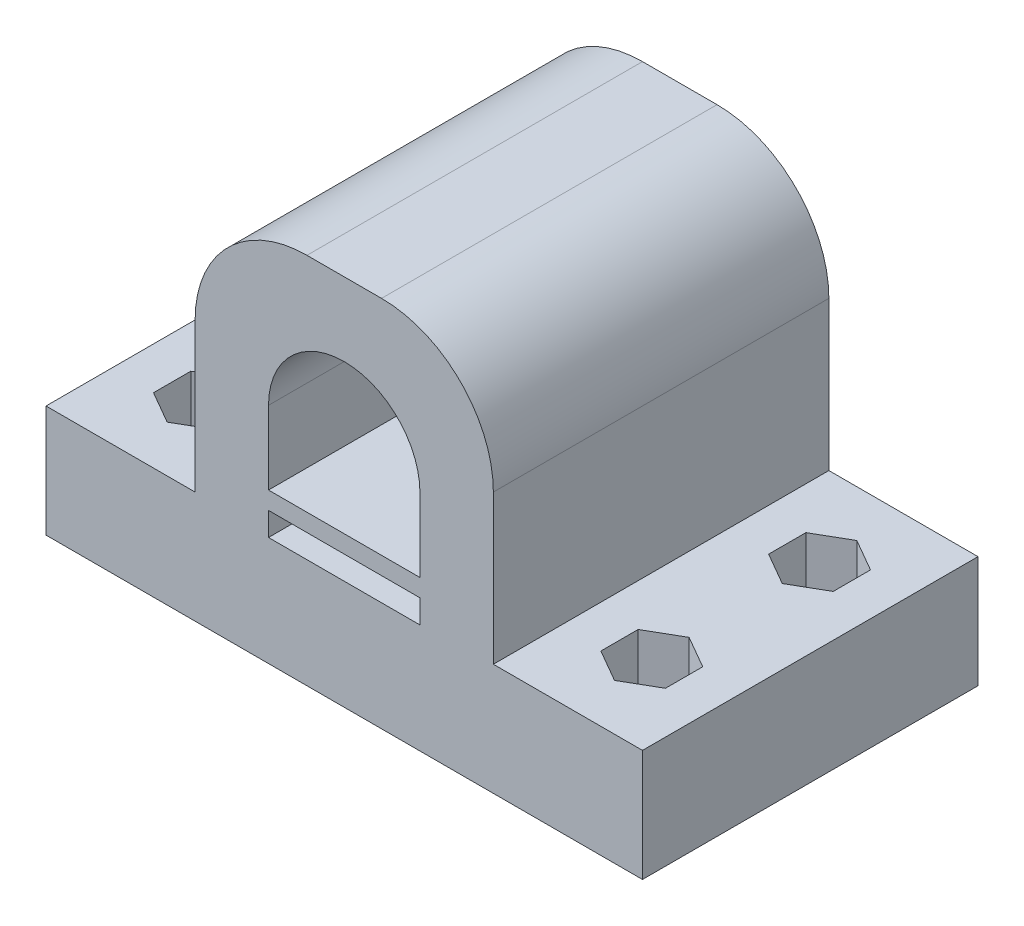
SolidWorks part; units mm, degrees
material "6063-T5"
ref_plane "Front Plane" through (0, 0, 0) normal (0, 0, 1) x (1, 0, 0)
ref_plane "Top Plane" through (0, 0, 0) normal (0, 1, 0) x (1, 0, 0)
ref_plane "Right Plane" through (0, 0, 0) normal (1, 0, 0) x (0, 0, -1)
sketch "Sketch1" plane through (0, 0, 0) normal (0, 1, 0) x (1, 0, 0)
  line L1 (-25.4, -14.2875) -> (25.4, -14.2875)
  line L2 (-25.4, -14.2875) -> (-25.4, 14.2875)
  line L3 (-25.4, 14.2875) -> (25.4, 14.2875)
  line L4 (25.4, -14.2875) -> (25.4, 14.2875)
  line L5 (-25.4, -14.2875) -> (25.4, 14.2875) construction
  line L6 (-25.4, 14.2875) -> (25.4, -14.2875) construction
  point P0 (0, 0)
  dimension "D1" = 50.8
  dimension "D2" = 28.575
extrude "Boss-Extrude1" add sketch "Sketch1" along normal blind 31.75
sketch "Sketch2" plane through (0, 0, 14.2875) normal (0, 0, 1) x (1, 0, 0)
  line L0 (-25.4, 0) -> (25.4, 0) construction
  line L1 (6.45, 9.3) -> (-6.45, 9.3)
  line L2 (0, 31.75) -> (0, 0) construction
  line L3 (25.4, 31.75) -> (12.7, 31.75)
  line L4 (25.4, 31.75) -> (25.4, 9.525)
  line L5 (25.4, 9.525) -> (12.7, 9.525)
  line L6 (12.7, 31.75) -> (12.7, 9.525)
  line L7 (-25.4, 31.75) -> (25.4, 31.75) construction
  line L8 (-25.4, 9.525) -> (-12.7, 9.525)
  line L9 (-25.4, 31.75) -> (-25.4, 9.525)
  line L10 (-25.4, 31.75) -> (-12.7, 31.75)
  line L11 (-12.7, 31.75) -> (-12.7, 9.525)
  line L12 (6.45, 9.3) -> (6.45, 11.3)
  line L13 (-6.45, 9.3) -> (-6.45, 11.3)
  line L14 (6.45, 11.3) -> (-6.45, 11.3)
  line L15 (6.45, 9.3) -> (-6.45, 11.3) construction
  line L16 (-6.45, 9.3) -> (6.45, 11.3) construction
  line L17 (6.45, 12.8) -> (-6.45, 12.8)
  line L18 (6.45, 12.8) -> (6.45, 19.05)
  line L19 (-6.45, 12.8) -> (-6.45, 19.05)
  arc A0 (6.45, 19.05) -> (-6.45, 19.05) centre (0, 19.05) ccw
  point P19 (0, 10.3)
  point P21 (0, 12.8)
  line M3 (25.4, 0) -> (25.4, 31.75)
  line M4 (25.4, 31.75) -> (-25.4, 31.75)
  line M5 (-25.4, 31.75) -> (-25.4, 0)
  dimension "D1" = 12.9
  dimension "D4" = 25.4
  dimension "D2" = 12.7
  dimension "D3" = 12.7
  dimension "D5" = 22.225
  dimension "D6" = 2
  dimension "D7" = 12.9
  dimension "D8" = 6.25
  dimension "D9" = 12.9
  dimension "D10" = 1.5
extrude "Cut-Extrude1" cut sketch "Sketch2" against normal up to surface (28.575 mm away) contours L11 L8 M4 M5 | L18 A0 L19 L17 | L12 L14 L13 L1 | L6 L5 M4 M3 up to face at (0, 15.875, -14.2875)
sketch "Sketch3" plane through (0, 0, 0) normal (0, -1, 0) x (1, 0, 0)
  line L0 (25.4, 14.2875) -> (25.4, -14.2875) construction
  line L1 (-25.4, 14.2875) -> (25.4, 14.2875) construction
  line L2 (-25.4, 0) -> (25.4, 0) construction
  line L3 (-25.4, -14.2875) -> (-25.4, 14.2875) construction
  line L4 (0, 14.2875) -> (0, -14.2875) construction
  line L5 (25.4, -14.2875) -> (-25.4, -14.2875) construction
  point P0 (19.05, 7.1438)
  point P13 (-19.05, 7.1437)
  point P14 (19.05, -7.1437)
  point P15 (-19.05, -7.1437)
  dimension "D1" = 6.35
  dimension "D2" = 7.1437
sketch "Sketch6" plane through (0, 31.75, 0) normal (0, 1, 0) x (1, 0, 0)
  point P0 (0, 0)
hole_wizard "Tap Drill for M5x0.8 Tap2" [suppressed] positions "Sketch8" profile "Sketch7" hole size "M5x0.8" standard "ANSI Metric"
sketch "Sketch8" [suppressed] plane through (0, 31.75, 0) normal (0, 1, 0) x (1, 0, 0)
  point P0 (0, 0)
sketch "Sketch7" plane through (0, 31.75, 0) normal (1, 0, 0) x (0, 0, 1)
  line L0 (0, 0) -> (0, 6.25)
  line L1 (0, 6.25) -> (2.1, 6.25)
  line L2 (2.1, 6.25) -> (2.1, 0)
  line L5 (2.1, 0) -> (0, 0)
  line L11 (0, -6.35) -> (0, 107.95) construction
  dimension "Thru Hole Dia." = 4.2
  dimension "Thru Hole Depth" = 6.25
fillet "Fillet2" radius 9.525 2 edges at (-12.7, 31.75, 0) (12.7, 31.75, 0)
sketch "Sketch9" plane through (0, 0, 0) normal (0, -1, 0) x (1, 0, 0)
  line L1 (16.3, -5.556) -> (16.3, -8.7315)
  line L2 (16.3, -8.7315) -> (19.05, -10.3192)
  line L3 (19.05, -10.3192) -> (21.8, -8.7315)
  line L4 (21.8, -8.7315) -> (21.8, -5.556)
  line L5 (21.8, -5.556) -> (19.05, -3.9683)
  line L6 (19.05, -3.9683) -> (16.3, -5.556)
  line L7 (16.3, 5.556) -> (19.05, 3.9683)
  line L8 (19.05, 3.9683) -> (21.8, 5.556)
  line L9 (21.8, 5.556) -> (21.8, 8.7315)
  line L10 (21.8, 8.7315) -> (19.05, 10.3192)
  line L11 (19.05, 10.3192) -> (16.3, 8.7315)
  line L12 (16.3, 8.7315) -> (16.3, 5.556)
  line L13 (-16.3, -8.7315) -> (-16.3, -5.556)
  line L14 (-16.3, -5.556) -> (-19.05, -3.9683)
  line L15 (-19.05, -3.9683) -> (-21.8, -5.556)
  line L16 (-21.8, -5.556) -> (-21.8, -8.7315)
  line L17 (-21.8, -8.7315) -> (-19.05, -10.3192)
  line L18 (-19.05, -10.3192) -> (-16.3, -8.7315)
  line L19 (-16.3, 5.556) -> (-16.3, 8.7315)
  line L20 (-16.3, 8.7315) -> (-19.05, 10.3192)
  line L21 (-19.05, 10.3192) -> (-21.8, 8.7315)
  line L22 (-21.8, 8.7315) -> (-21.8, 5.556)
  line L23 (-21.8, 5.556) -> (-19.05, 3.9683)
  line L24 (-19.05, 3.9683) -> (-16.3, 5.556)
  circle A0 centre (19.05, -7.1437) radius 2.75 construction
  circle A1 centre (19.05, 7.1438) radius 2.75 construction
  circle A2 centre (-19.05, -7.1437) radius 2.75 construction
  circle A3 centre (-19.05, 7.1437) radius 2.75 construction
  dimension "D1" = 5.5
  dimension "D2" = 5.5
  dimension "D3" = 5.5
  dimension "D4" = 5.5
extrude "Cut-Extrude2" cut sketch "Sketch9" against normal up to next
equation "\"D4@Sketch2\"=\"D1@Sketch1\"/2"
equation "\"D1@Sketch3\"=\"D3@Sketch2\"/2"
equation "\"D2@Sketch3\"=\"D2@Sketch1\"/4"
equation "\"D7@Sketch2\"=\"D1@Sketch2\""
equation "\"D9@Sketch2\"=\"D7@Sketch2\""
